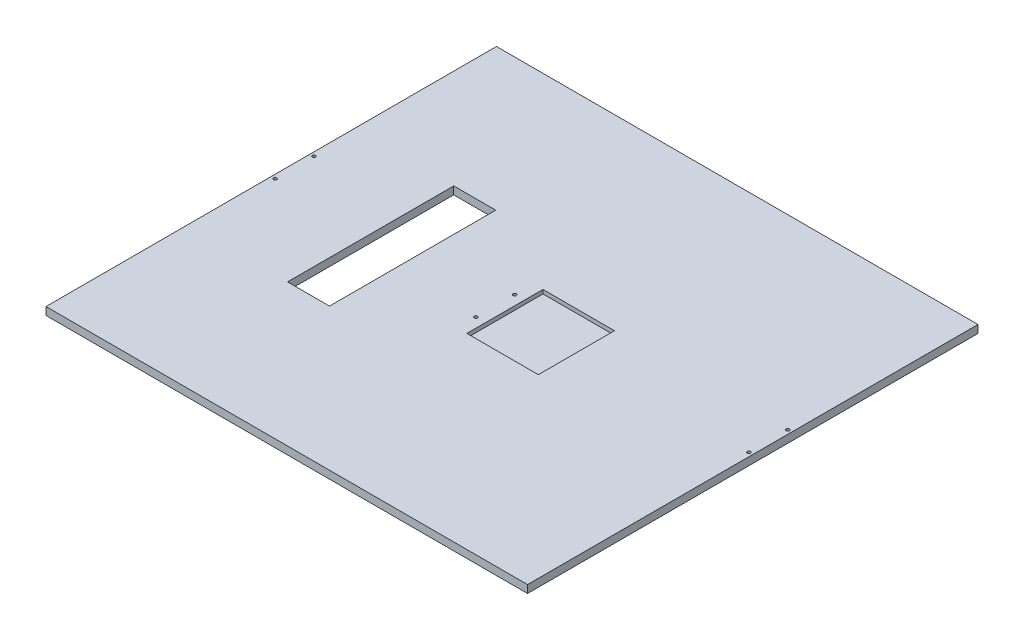
SolidWorks part; units mm, degrees
material "1.4511 (X3CrNb17)"
ref_plane "前视基准面" through (0, 0, 0) normal (0, 0, 1) x (1, 0, 0)
ref_plane "上视基准面" through (0, 0, 0) normal (0, 1, 0) x (1, 0, 0)
ref_plane "右视基准面" through (0, 0, 0) normal (1, 0, 0) x (0, 0, -1)
sketch "草图1" plane through (0, 0, 0) normal (0, 1, 0) x (1, 0, 0)
  line L1 (-310, 290) -> (310, 290)
  line L2 (-310, 290) -> (-310, -290)
  line L3 (-310, -290) -> (310, -290)
  line L4 (310, 290) -> (310, -290)
  line L5 (-310, 290) -> (310, -290) construction
  line L6 (-310, -290) -> (310, 290) construction
  point P0 (0, 0)
  dimension "D1" = 620
  dimension "D2" = 580
extrude "凸台-拉伸1" add sketch "草图1" along normal blind 10
sketch "草图2" plane through (0, 10, 0) normal (0, 1, 0) x (1, 0, 0)
  line L1 (-305, 50) -> (305, 50) construction
  line L2 (-305, 50) -> (-305, 0) construction
  line L3 (-305, 0) -> (305, 0) construction
  line L4 (305, 50) -> (305, 0) construction
  line L5 (-305, 50) -> (305, 0) construction
  line L6 (-305, 0) -> (305, 50) construction
  dimension "D1" = 50
  dimension "D2" = 610
hole_wizard "M5 螺纹孔1" positions "草图3" profile "草图4" tap size "M5" standard "GB"
sketch "草图3" plane through (0, 10, 0) normal (0, 1, 0) x (1, 0, 0)
  point P0 (-305, 50)
  point P3 (-305, 0)
  point P6 (305, 0)
  point P9 (305, 50)
sketch "草图4" plane through (-305, 10, -50) normal (1, 0, 0) x (0, 0, 1)
  line L0 (0, 0) -> (0, 13.4618)
  line L1 (0, 13.4618) -> (2.1, 12.2)
  line L2 (2.1, 12.2) -> (2.1, 0)
  line L5 (2.1, 0) -> (0, 0)
  line L10 (0, 13.4618) -> (-2.1, 12.2) construction
  line L11 (0, -6.35) -> (0, 107.95) construction
  dimension "螺纹孔钻头直径" = 4.2
  dimension "螺纹孔钻头深度" = 12.2
  dimension "导头角度" = 118
cosmetic thread "孔螺蚊线1" parameters "D1"=8.2, "D2"=5
cosmetic thread "孔螺蚊线2" parameters "D1"=8.2, "D2"=5
cosmetic thread "孔螺蚊线3" parameters "D1"=8.2, "D2"=5
cosmetic thread "孔螺蚊线4" parameters "D1"=8.2, "D2"=5
sketch "草图5" plane through (0, 0, 0) normal (0, -1, 0) x (1, 0, 0)
  line L0 (-310, -290) -> (-310, 290) construction
  line L1 (-182, 107) -> (-128, 107)
  line L2 (-182, 107) -> (-182, -107)
  line L3 (-182, -107) -> (-128, -107)
  line L4 (-128, 107) -> (-128, -107)
  line L5 (-182, 107) -> (-128, -107) construction
  line L6 (-182, -107) -> (-128, 107) construction
  dimension "D1" = 54
  dimension "D2" = 214
  dimension "D3" = 128
extrude "切除-拉伸1" cut sketch "草图5" against normal through all
sketch "草图6" plane through (0, 0, 0) normal (0, -1, 0) x (1, 0, 0)
  line L0 (-310, 290) -> (310, 290) construction
  line L1 (-310, -290) -> (-310, 290) construction
  line L2 (50, 0) -> (-21.6, 0) construction
  line L3 (-21.6, 25) -> (-21.6, -25) construction
  point P0 (50, 0)
  point P11 (-21.6, 0)
  dimension "D1" = 290
  dimension "D2" = 360
  dimension "D3" = 71.6
  dimension "D4" = 50
hole_wizard "M5 螺纹孔2" positions "草图7" profile "草图8" tap size "M5" standard "GB" end condition through all
sketch "草图7" plane through (0, 0, 0) normal (0, -1, 0) x (-1, 0, 0)
  point P0 (21.6, -25)
  point P3 (21.6, 25)
cosmetic thread "孔螺蚊线5" parameters "D2"=5
cosmetic thread "孔螺蚊线6" parameters "D2"=5
sketch "草图8" plane through (-21.6, 0, 25) normal (1, 0, 0) x (0, 0, -1)
  line L0 (0, 0) -> (0, 10)
  line L1 (0, 10) -> (2.1, 10)
  line L2 (2.1, 10) -> (2.1, 0)
  line L5 (2.1, 0) -> (0, 0)
  line L11 (0, -6.35) -> (0, 107.95) construction
  dimension "通孔螺纹孔钻头直径" = 4.2
  dimension "通孔螺纹孔钻头深度" = 10
sketch "草图10" plane through (0, 10, 0) normal (0, 1, 0) x (1, 0, 0)
  line L0 (-9.1, 49) -> (-9.1, -49)
  line L2 (-9.1, 49) -> (82.9, 49)
  line L3 (82.9, 49) -> (82.9, -49)
  line L4 (82.9, -49) -> (-9.1, -49)
  point P3 (-9.1, 0)
  dimension "D1" = 12.5
  dimension "D2" = 98
  dimension "D3" = 92
extrude "切除-拉伸2" cut sketch "草图10" against normal blind 5
